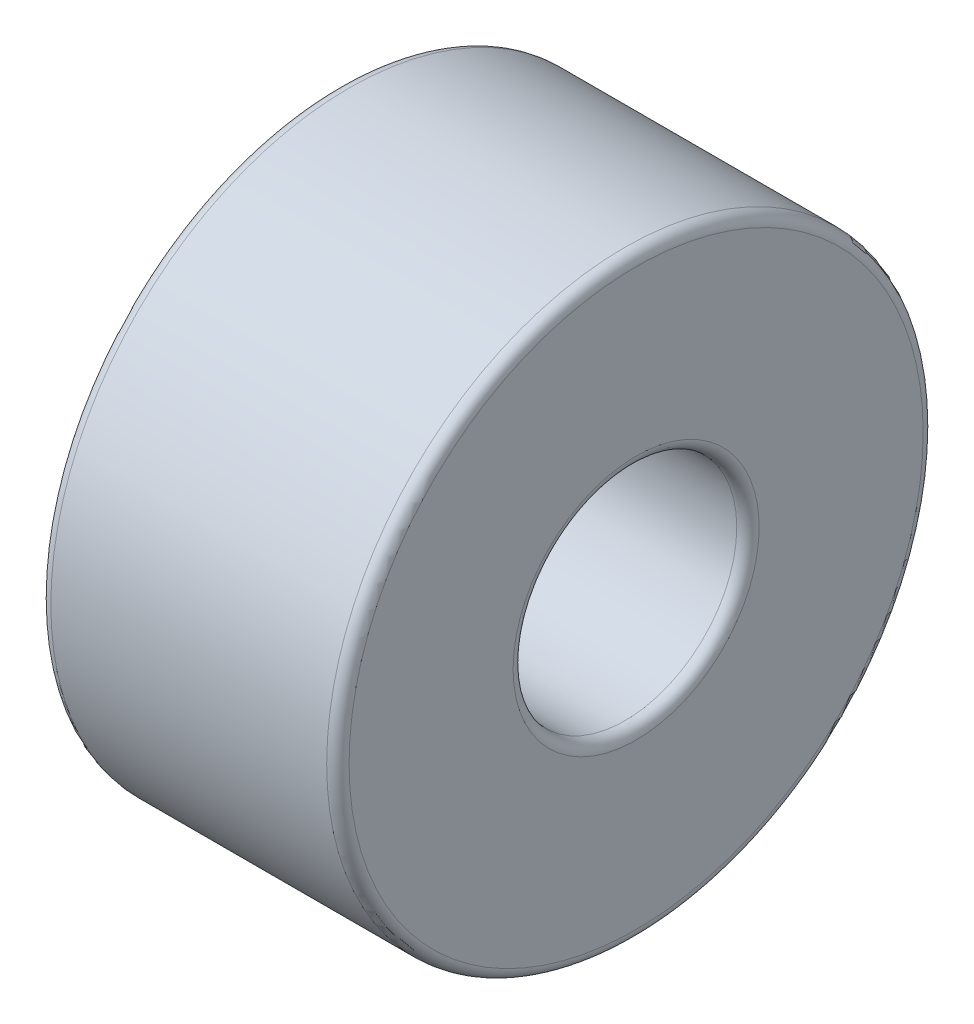
SolidWorks part; units mm, degrees
ref_plane "Front Plane" through (0, 0, 0) normal (0, 0, 1) x (1, 0, 0)
ref_plane "Top Plane" through (0, 0, 0) normal (0, 1, 0) x (1, 0, 0)
ref_plane "Right Plane" through (0, 0, 0) normal (1, 0, 0) x (0, 0, -1)
ref_plane "Plane4" through (0, 0, 0) normal (0, 0, -1) x (-1, 0, 0)
sketch "Sketch1" plane through (0, 0, 0) normal (0, 0, -1) x (-1, 0, 0)
  line L0 (-0.75, 2.8175) -> (-0.75, 2.6825)
  line L1 (-0.75, 2.6825) -> (-1.9325, 2.6825)
  line L2 (-1.9325, 2.6825) -> (-1.9325, 2.3333)
  line L3 (-1.9325, 2.3333) -> (-2.0675, 2.3333)
  line L4 (-2.0675, 2.3333) -> (-2.0675, 2.6825)
  line L5 (-2.0675, 2.6825) -> (-3.25, 2.6825)
  line L6 (-3.25, 2.6825) -> (-3.25, 2.8175)
  line L7 (-3.25, 2.8175) -> (-2.0675, 2.8175)
  line L8 (-2.0675, 2.8175) -> (-2.0675, 3.1667)
  line L9 (-2.0675, 3.1667) -> (-1.9325, 3.1667)
  line L10 (-1.9325, 3.1667) -> (-1.9325, 2.8175)
  line L11 (-1.9325, 2.8175) -> (-0.75, 2.8175)
  line L12 (-3.85, 1.5) -> (-0.15, 1.5)
  line L13 (0, 1.65) -> (0, 3.85)
  line L14 (-0.15, 4) -> (-3.85, 4)
  line L15 (-4, 3.85) -> (-4, 1.65)
  line L16 (-4, 0) -> (0, 0) construction
  arc A0 (-4, 1.65) -> (-3.85, 1.5) centre (-3.85, 1.65) ccw
  arc A1 (-0.15, 1.5) -> (0, 1.65) centre (-0.15, 1.65) ccw
  arc A2 (0, 3.85) -> (-0.15, 4) centre (-0.15, 3.85) ccw
  arc A3 (-3.85, 4) -> (-4, 3.85) centre (-3.85, 3.85) ccw
revolve "Revolve1" add sketch "Sketch1" angle 360 about L16
